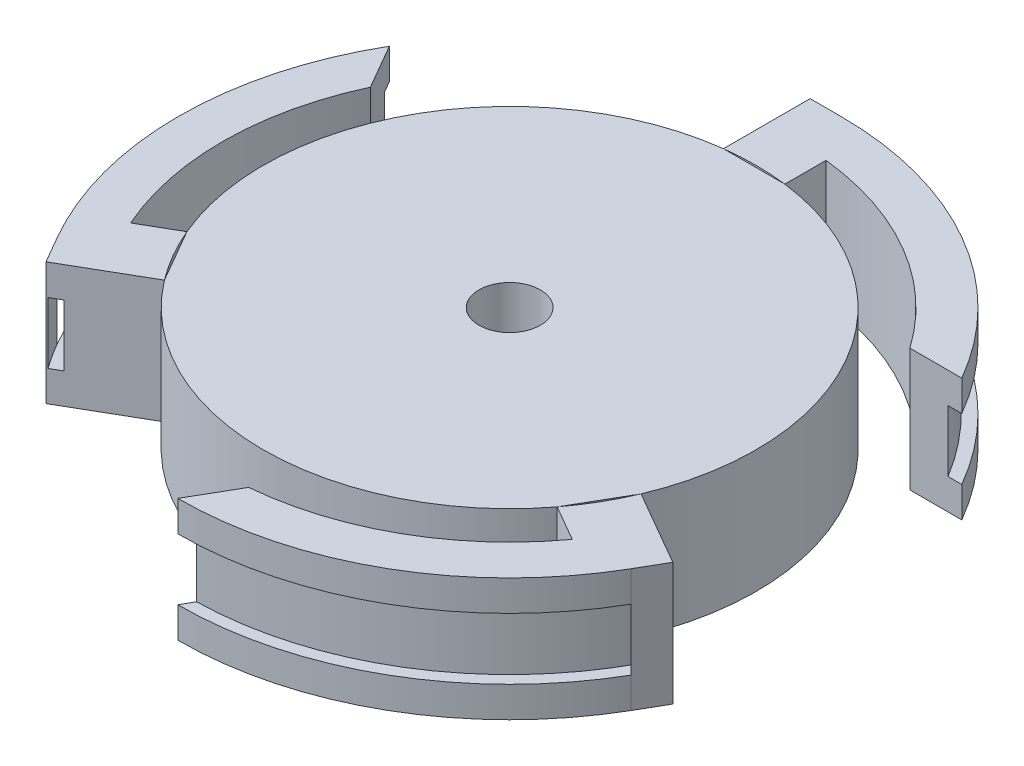
SolidWorks part; units mm, degrees
ref_plane "Front Plane" through (0, 0, 0) normal (0, 0, 1) x (1, 0, 0)
ref_plane "Top Plane" through (0, 0, 0) normal (0, 1, 0) x (1, 0, 0)
ref_plane "Right Plane" through (0, 0, 0) normal (1, 0, 0) x (0, 0, -1)
sketch "Sketch1" plane through (0, 0, 0) normal (0, 1, 0) x (1, 0, 0)
  line L0 (0, 0) -> (0, 26.967) construction
  line L1 (19.1568, 13.4338) -> (23.3827, 13.4338)
  line L2 (-2.5, 26.967) -> (2.5, 26.967)
  line L3 (-2.5, 26.967) -> (-2.5, 19.9066)
  line L4 (-2.5, 19.9066) -> (2.5, 19.9066)
  line L5 (2.5, 26.967) -> (2.5, 19.9066)
  line L6 (24.6041, -11.3184) -> (18.4897, -7.7883)
  line L7 (24.6041, -11.3184) -> (22.1041, -15.6486)
  line L8 (22.1041, -15.6486) -> (15.9897, -12.1184)
  line L9 (18.4897, -7.7883) -> (15.9897, -12.1184)
  line L10 (2.0557, -23.3072) -> (-0.0573, -26.9669)
  line L11 (-22.1041, -15.6486) -> (-15.9897, -12.1184)
  line L12 (-22.1041, -15.6486) -> (-24.6041, -11.3184)
  line L13 (-24.6041, -11.3184) -> (-18.4897, -7.7883)
  line L14 (-15.9897, -12.1184) -> (-18.4897, -7.7883)
  line L15 (-21.2124, 9.8733) -> (-23.3254, 13.5331)
  circle A0 centre (0, 0) radius 20.063
  circle A1 centre (0, 0) radius 33.5 construction
  arc A2 (0, 26.967) -> (23.3827, 13.4338) centre (0, 0) cw
  arc A3 (2.5, 23.2637) -> (19.1568, 13.4338) centre (0, 0) cw
  arc A4 (18.897, -13.7969) -> (2.0557, -23.3072) centre (0, 0) cw
  arc A5 (23.3541, -13.4835) -> (-0.0573, -26.9669) centre (0, 0) cw
  arc A6 (-21.397, -9.4668) -> (-21.2124, 9.8733) centre (0, 0) cw
  arc A7 (-23.3541, -13.4835) -> (-23.3254, 13.5331) centre (0, 0) cw
  point P31 (0, 0)
  dimension "D1" = 3
extrude "Boss-Extrude1" add sketch "Sketch1" along normal mid plane 10 contours L9 A0 L4 L14 | A7 L12 L11 A0 L13 | A7 L13 A6 L15 | A5 L7 L6 A0 L8 | A5 L8 A4 L10 | L5 A3 L1 A2 | A2 L2 L3 A0 L5
sketch "Sketch2" plane through (0, 0, 0) normal (0, 1, 0) x (1, 0, 0)
  circle A0 centre (0, 0) radius 26.967
  circle A1 centre (0, 0) radius 26
extrude "Cut-Extrude1" cut sketch "Sketch2" against normal mid plane 5
sketch "Sketch3" plane through (0, 5, 0) normal (0, 1, 0) x (1, 0, 0)
  circle A0 centre (0, 0) radius 2.5
extrude "Cut-Extrude2" cut sketch "Sketch3" against normal mid plane 15
sketch "Sketch4" plane through (0, -2.5, 0) normal (0, 1, 0) x (1, 0, 0)
  circle A0 centre (0, 0) radius 7.5
extrude "Cut-Extrude3" cut sketch "Sketch4" against normal mid plane 7
